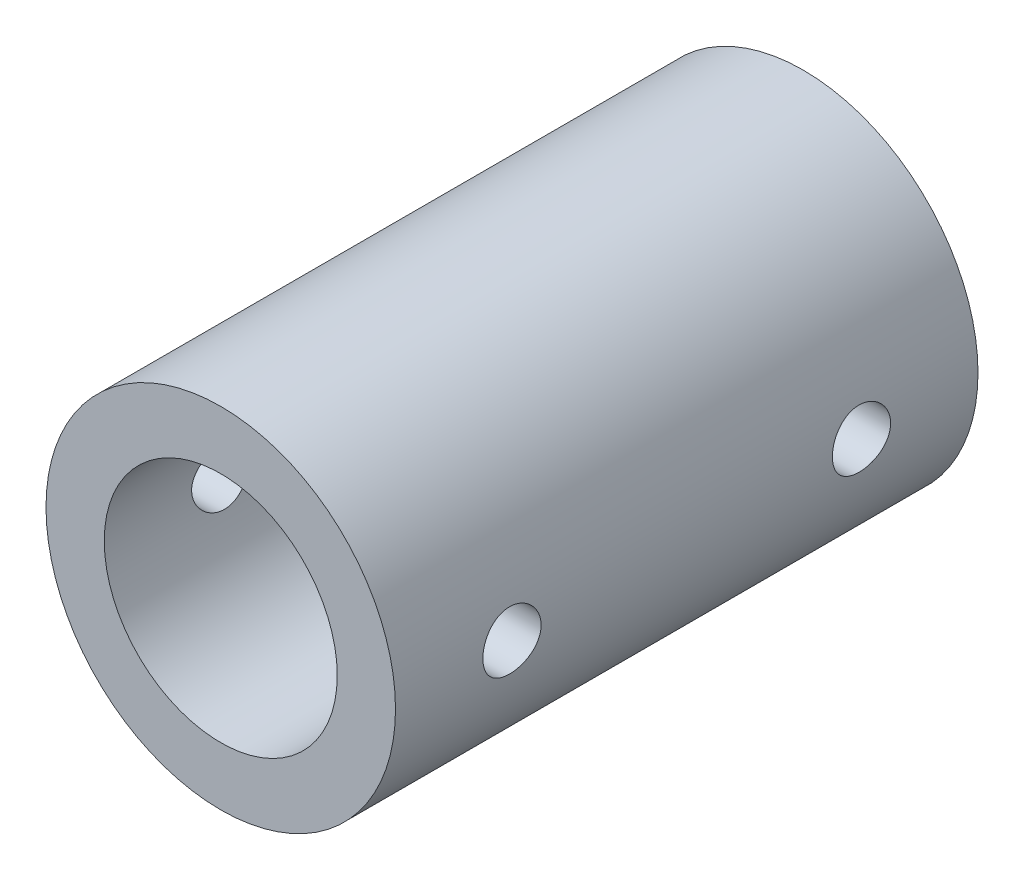
SolidWorks part; units mm, degrees
ref_plane "Front Plane" through (0, 0, 0) normal (0, 0, 1) x (1, 0, 0)
ref_plane "Top Plane" through (0, 0, 0) normal (0, 1, 0) x (1, 0, 0)
ref_plane "Right Plane" through (0, 0, 0) normal (1, 0, 0) x (0, 0, -1)
sketch "Sketch1" plane through (0, 0, 0) normal (0, 0, 1) x (1, 0, 0)
  circle A0 centre (0, 0) radius 6
  circle A1 centre (0, 0) radius 4
  dimension "D1" = 12
  dimension "D2" = 8
extrude "Boss-Extrude1" add sketch "Sketch1" along normal mid plane 20
sketch "Sketch2" plane through (0, 0, 0) normal (1, 0, 0) x (0, 0, -1)
  circle A0 centre (-6, 0) radius 1
  dimension "D1" = 2
  dimension "D2" = 6
  dimension "D3" = 0
extrude "Cut-Extrude1" cut sketch "Sketch2" against normal mid plane 20
mirror "Mirror1" about plane through (0, 0, 0) normal (0, 0, 1) of "Cut-Extrude1"
